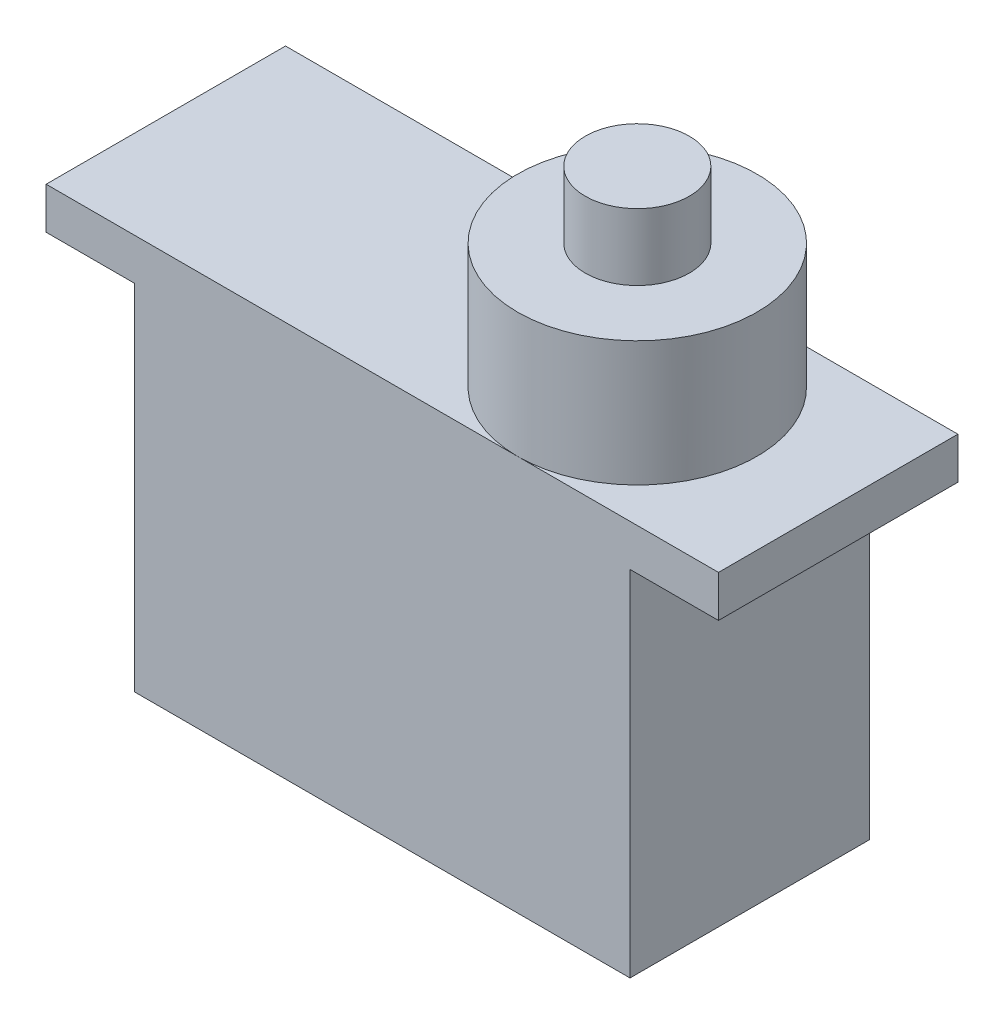
SolidWorks part; units mm, degrees
ref_plane "Front Plane" through (0, 0, 0) normal (0, 0, 1) x (1, 0, 0)
ref_plane "Top Plane" through (0, 0, 0) normal (0, 1, 0) x (1, 0, 0)
ref_plane "Right Plane" through (0, 0, 0) normal (1, 0, 0) x (0, 0, -1)
sketch "Sketch1" plane through (0, 0, 0) normal (0, 1, 0) x (1, 0, 0)
  line L1 (0, 0) -> (23.8, 0)
  line L2 (0, 0) -> (0, 11.5)
  line L3 (0, 11.5) -> (23.8, 11.5)
  line L4 (23.8, 0) -> (23.8, 11.5)
  dimension "D1" = 23.8
  dimension "D2" = 11.5
extrude "Boss-Extrude1" add sketch "Sketch1" along normal blind 17
sketch "Sketch2" plane through (0, 17, 0) normal (0, 1, 0) x (1, 0, 0)
  line L0 (0, 0) -> (23.8, 0) construction
  line L1 (-4.25, 11.5) -> (28.05, 11.5)
  line L2 (-4.25, 11.5) -> (-4.25, 0)
  line L3 (-4.25, 0) -> (28.05, 0)
  line L4 (28.05, 11.5) -> (28.05, 0)
  line L5 (23.8, 11.5) -> (0, 11.5) construction
  point P8 (11.9, 0)
  point P9 (0, 0)
  dimension "D1" = 32.3
extrude "Boss-Extrude2" add sketch "Sketch2" along normal blind 2
sketch "Sketch3" plane through (0, 19, 0) normal (0, 1, 0) x (1, 0, 0)
  line L0 (-4.25, 0) -> (28.05, 0) construction
  line L1 (28.05, 11.5) -> (-4.25, 11.5) construction
  line L2 (23.8, 0) -> (23.8, 11.5) construction
  circle A0 centre (18.4, 5.75) radius 5.75
  point P6 (0, 0)
  dimension "D1" = 5.4
extrude "Boss-Extrude3" add sketch "Sketch3" along normal blind 6
sketch "Sketch4" plane through (0, 25, 0) normal (0, 1, 0) x (1, 0, 0)
  circle A0 centre (18.4, 5.75) radius 2.5
  circle A1 centre (18.4, 5.75) radius 5.75 construction
  dimension "D1" = 5
extrude "Boss-Extrude4" add sketch "Sketch4" along normal blind 3.2
